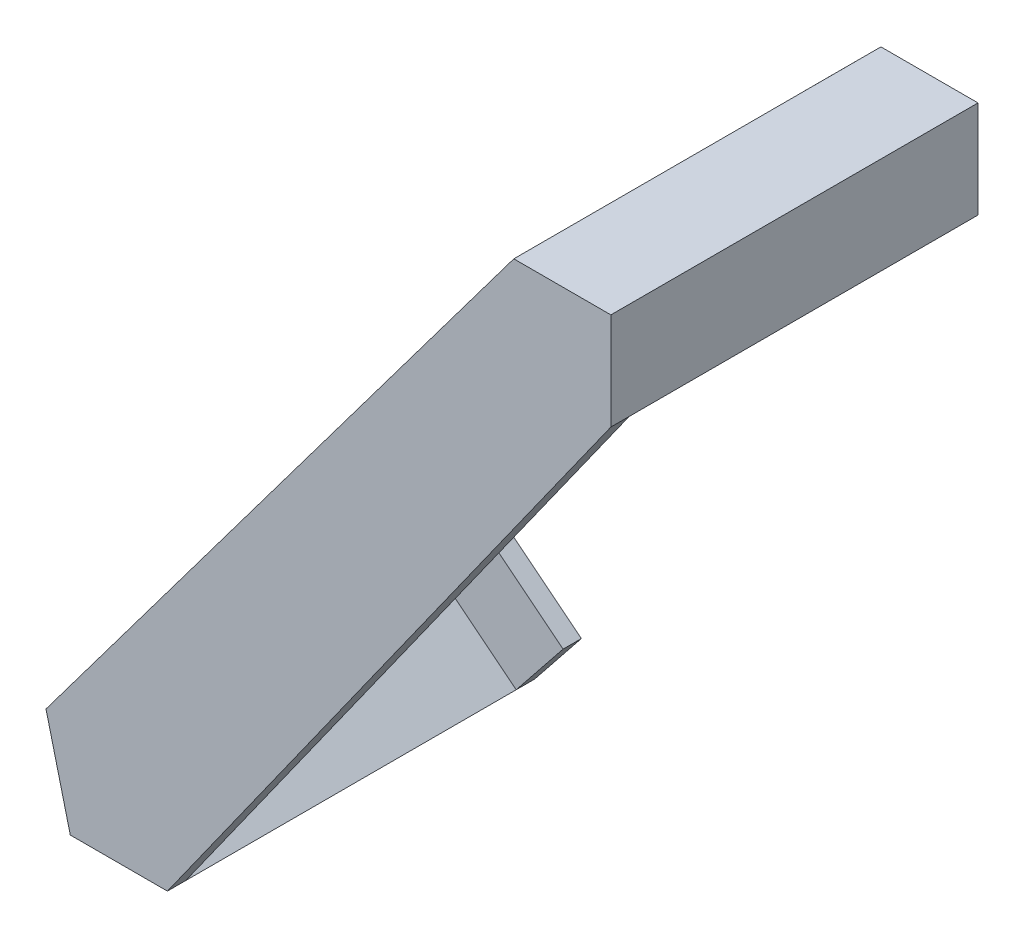
SolidWorks part; units mm, degrees
ref_plane "Front Plane" through (0, 0, 0) normal (0, 0, 1) x (1, 0, 0)
ref_plane "Top Plane" through (0, 0, 0) normal (0, 1, 0) x (1, 0, 0)
ref_plane "Right Plane" through (0, 0, 0) normal (1, 0, 0) x (0, 0, -1)
sketch "Sketch1" plane through (0, 0, 0) normal (0, 0, 1) x (1, 0, 0)
  line L0 (-18.9162, -42.7196) -> (40.1318, 36.011) construction
  line L1 (29.5286, 36.011) -> (-21.5694, -32.1196)
  line L2 (29.5286, 36.011) -> (40.1318, 36.011)
  line L4 (-18.9162, -42.7196) -> (-8.3062, -42.7196)
  line L5 (40.1318, 36.011) -> (40.1318, 25.401)
  line L6 (40.1318, 25.401) -> (-8.3062, -42.7196)
  line L7 (-21.5694, -32.1196) -> (-18.9162, -42.7196)
  line L8 (29.5286, 36.011) -> (40.1318, 25.401) construction
  line L9 (-21.5694, -32.1196) -> (-8.3062, -42.7196) construction
  dimension "D1" = 10.61
  dimension "D2" = 10.6032
  dimension "D3" = 15
  dimension "D4" = 10.6
  dimension "D5" = 10.61
extrude "Boss-Extrude1" add sketch "Sketch1" along normal blind 2
sketch "Sketch2" plane through (0, 0, 0) normal (0, 0, -1) x (-1, 0, 0)
  line L0 (-40.1318, 25.401) -> (-29.5286, 36.011)
  line L1 (8.3062, -42.7196) -> (21.5694, -32.1196)
  line L2 (-40.1318, 25.401) -> (-40.1318, 36.011)
  line L3 (-40.1318, 36.011) -> (-29.5286, 36.011)
  line L4 (21.5694, -32.1196) -> (18.9162, -42.7196)
  line L5 (18.9162, -42.7196) -> (8.3062, -42.7196)
extrude "Boss-Extrude2" add sketch "Sketch2" along normal blind 38.1
sketch "Sketch3" plane through (0, 0, -38.1) normal (0, 0, -1) x (-1, 0, 0)
  line L0 (21.5694, -32.1196) -> (8.3062, -42.7196)
  line L5 (21.5694, -32.1196) -> (16.4573, -25.7232)
  line L6 (8.3062, -42.7196) -> (3.1941, -36.3232)
  line L7 (16.4573, -25.7232) -> (3.1941, -36.3232)
  line L8 (21.5694, -32.1196) -> (8.3062, -42.7196) construction
  line L9 (18.9162, -42.7196) -> (21.5694, -32.1196) construction
  line L10 (-29.5286, 36.011) -> (-40.1318, 25.401)
  line L11 (-29.5286, 36.011) -> (-23.2606, 29.7471)
  line L12 (-40.1318, 25.401) -> (-33.8638, 19.1371)
  line L13 (-23.2606, 29.7471) -> (-33.8638, 19.1371)
extrude "Boss-Extrude3" add sketch "Sketch3" against normal blind 2
